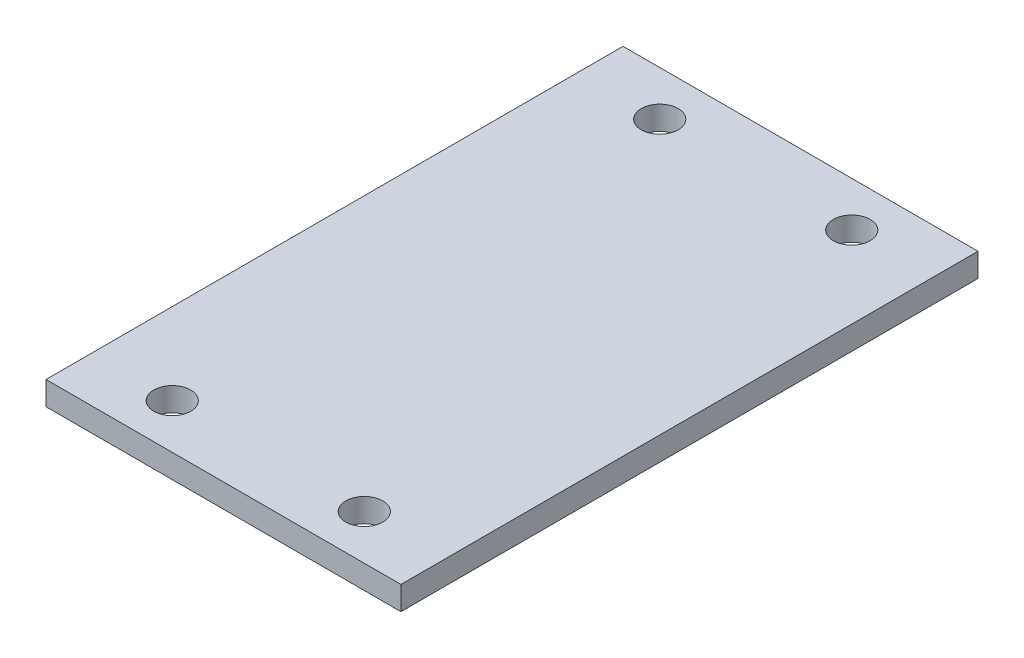
SolidWorks part; units mm, degrees
ref_plane "Front Plane" through (0, 0, 0) normal (0, 0, 1) x (1, 0, 0)
ref_plane "Top Plane" through (0, 0, 0) normal (0, 1, 0) x (1, 0, 0)
ref_plane "Right Plane" through (0, 0, 0) normal (1, 0, 0) x (0, 0, -1)
sketch "Sketch1" plane through (0, 0, 0) normal (0, 1, 0) x (1, 0, 0)
  line L1 (0, 0) -> (24.0284, 0)
  line L2 (0, 0) -> (0, 39.0652)
  line L3 (0, 39.0652) -> (24.0284, 39.0652)
  line L4 (24.0284, 0) -> (24.0284, 39.0652)
  circle A0 centre (5.5142, 36.0326) radius 1.25
  circle A1 centre (5.5142, 3.0326) radius 1.25
  circle A2 centre (18.5142, 36.0326) radius 1.25
  circle A3 centre (18.5142, 3.0326) radius 1.25
  dimension "D5" = 2.5
  dimension "D1" = 24.0284
  dimension "D2" = 39.0652
  dimension "D3" = 13
  dimension "D4" = 33
  dimension "D6" = 3.0326
  dimension "D7" = 5.5142
extrude "Boss-Extrude1" add sketch "Sketch1" along normal blind 1.6
equation "\"D6@Sketch1\"=(\"D2@Sketch1\"-\"D4@Sketch1\")/2"
equation "\"D7@Sketch1\"=(\"D1@Sketch1\"-\"D3@Sketch1\")/2"
